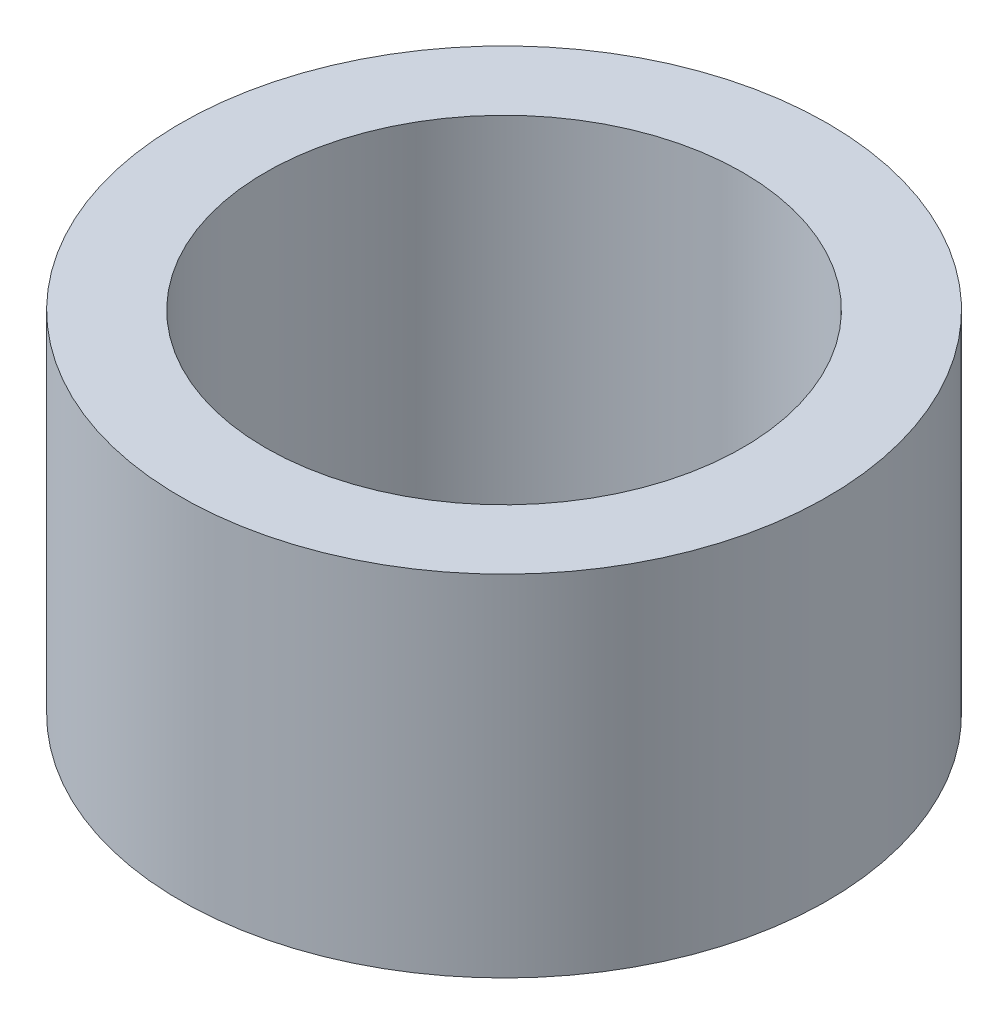
SolidWorks part; units mm, degrees
material "Nylon 101"
ref_plane "Front Plane" through (0, 0, 0) normal (0, 0, 1) x (1, 0, 0)
ref_plane "Top Plane" through (0, 0, 0) normal (0, 1, 0) x (1, 0, 0)
ref_plane "Right Plane" through (0, 0, 0) normal (1, 0, 0) x (0, 0, -1)
ref_plane "Plane1" through (0, 7.112, 0) normal (0, 1, 0) x (1, 0, 0)
sketch "Sketch1" plane through (0, 7.112, 0) normal (0, 1, 0) x (1, 0, 0)
  circle A0 centre (0, 0) radius 4.8514
  circle A1 centre (0, 0) radius 6.5786
extrude "Boss-Extrude1" add sketch "Sketch1" against normal blind 7.112
